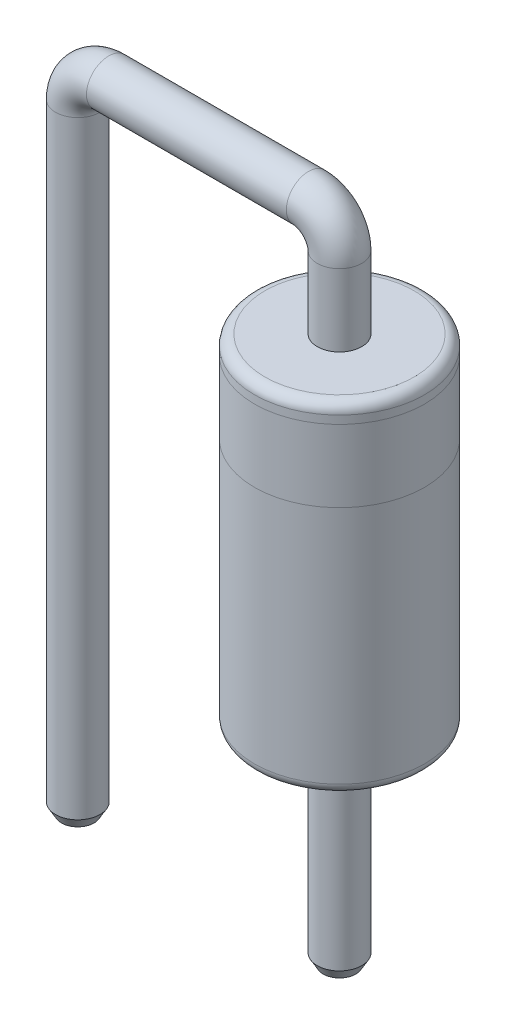
SolidWorks part; units mm, degrees
ref_plane "Front Plane" through (0, 0, 0) normal (0, 0, 1) x (1, 0, 0)
ref_plane "Top Plane" through (0, 0, 0) normal (0, 1, 0) x (1, 0, 0)
ref_plane "Right Plane" through (0, 0, 0) normal (1, 0, 0) x (0, 0, -1)
sketch "Sketch1" plane through (0, 0, 0) normal (0, 1, 0) x (1, 0, 0)
  circle A0 centre (0, 0) radius 0.2159
  dimension "D1" = 0.4318
sketch "Sketch2" plane through (0, 0, 0) normal (0, 0, 1) x (1, 0, 0)
  line L0 (0, 0) -> (0, 6.002)
  line L1 (-0.3, 6.302) -> (-2.24, 6.302)
  line L2 (-2.54, 6.002) -> (-2.54, 0)
  line L3 (0.2159, 0) -> (-0.2159, 0) construction
  arc A0 (-2.24, 6.302) -> (-2.54, 6.002) centre (-2.24, 6.002) ccw
  arc A1 (-0.3, 6.302) -> (0, 6.002) centre (-0.3, 6.002) cw
  point P8 (-2.54, 2)
  point P11 (-5.08, 2)
  dimension "D1" = 0.3
  dimension "D2" = 6.302
  dimension "D3" = 2.54
sweep "Sweep1" add profiles "Sketch1" path "Sketch2"
sketch3d "3DSketch4" plane through (0, 0, 0) normal (0, 0, 1) x (1, 0, 0)
  dimension "D1" = 2
sketch "Sketch3" plane through (1.111, 2, 0) normal (0, 1, 0) x (0, 0, -1)
  circle A0 centre (0, 1.111) radius 0.825
  dimension "D1" = 1.65
extrude "Extrude1" add sketch "Sketch3" along normal blind 3.302
fillet "Fillet1" radius 0.1 2 edges at (0, 5.302, 0.825) (0, 2, 0.825)
chamfer "Chamfer1" distance 0.1 angle 30 2 edges at (-2.54, 0, 0.2159) (0, 0, 0.2159)
sketch3d "3DSketch3" plane through (0, 0, 0) normal (0, 0, 1) x (1, 0, 0)
  dimension "D1" = 2
sketch "Sketch4" plane through (0, 0, 2) normal (0, 0, 1) x (1, 0, 0)
  line L1 (1.0259, 5.1241) -> (-1.0657, 5.1241)
  line L2 (1.0259, 5.1241) -> (1.0259, 4.4241)
  line L3 (1.0259, 4.4241) -> (-1.0657, 4.4241)
  line L4 (-1.0657, 5.1241) -> (-1.0657, 4.4241)
  dimension "D1" = 0.7
split line "Split Line1"
